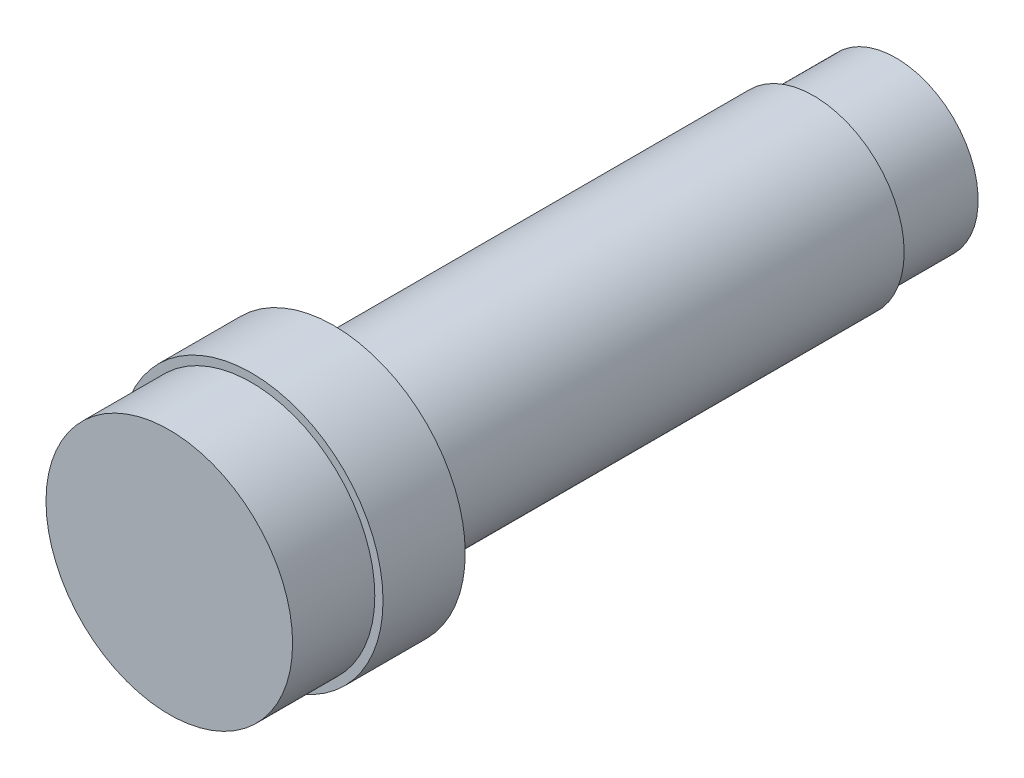
SolidWorks part; units mm, degrees
ref_plane "正面" through (0, 0, 0) normal (0, 0, 1) x (1, 0, 0)
ref_plane "平面" through (0, 0, 0) normal (0, 1, 0) x (1, 0, 0)
ref_plane "右側面" through (0, 0, 0) normal (1, 0, 0) x (0, 0, -1)
sketch "ｽｹｯﾁ1" plane through (0, 0, 0) normal (0, 0, 1) x (1, 0, 0)
  circle A0 centre (0, 0) radius 5.5
  dimension "D1" = 11
extrude "ﾎﾞｽ - 押し出し1" add sketch "ｽｹｯﾁ1" along normal blind 34.2
sketch "ｽｹｯﾁ2" plane through (0, 0, 34.2) normal (0, 0, 1) x (1, 0, 0)
  circle A0 centre (0, 0) radius 8
  dimension "D1" = 16
extrude "ﾎﾞｽ - 押し出し2" add sketch "ｽｹｯﾁ2" against normal blind 5
sketch "ｽｹｯﾁ3" plane through (0, 0, 34.2) normal (0, 0, 1) x (1, 0, 0)
  circle A0 centre (0, 0) radius 7.5
  dimension "D1" = 15
extrude "ﾎﾞｽ - 押し出し3" add sketch "ｽｹｯﾁ3" along normal blind 5
sketch "ｽｹｯﾁ5" plane through (0, 0, 0) normal (0, 0, -1) x (-1, 0, 0)
  circle A0 centre (0, 0) radius 5
  dimension "D1" = 10
extrude "ﾎﾞｽ - 押し出し4" add sketch "ｽｹｯﾁ5" along normal blind 5
